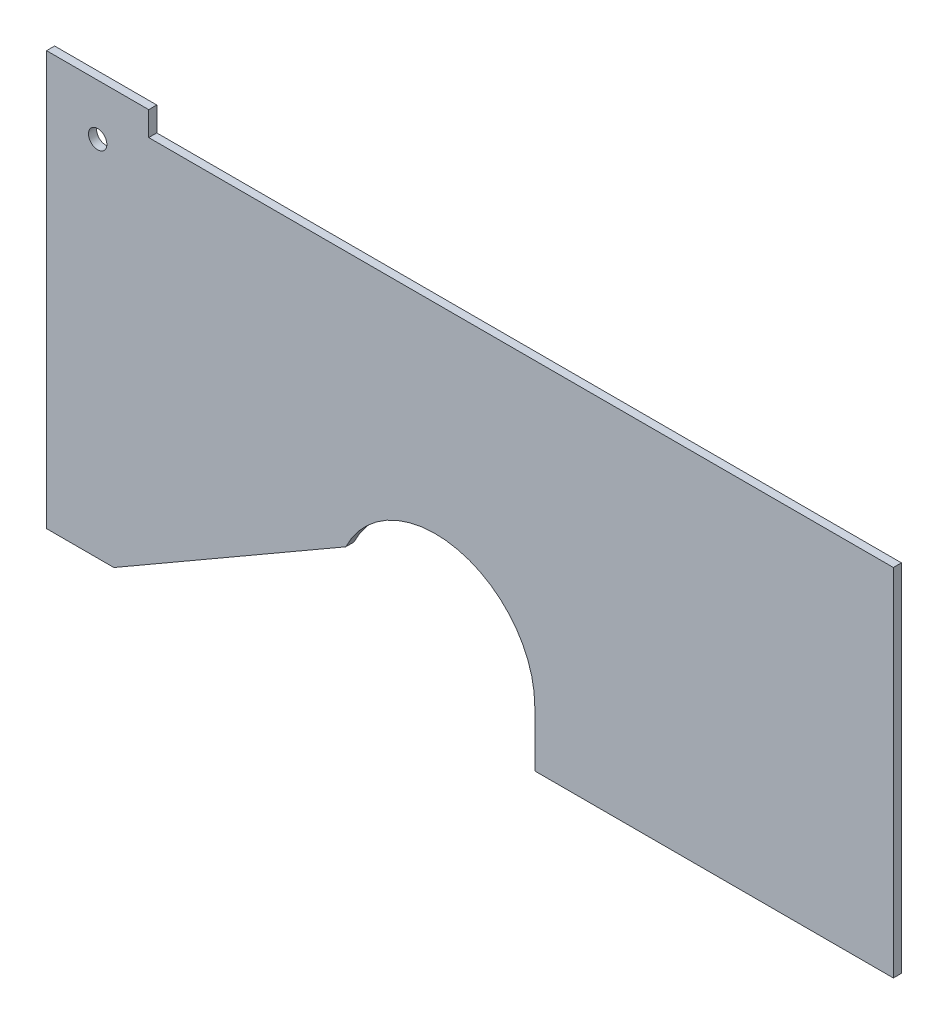
SolidWorks part; units mm, degrees
ref_plane "Front Plane" through (0, 0, 0) normal (0, 0, 1) x (1, 0, 0)
ref_plane "Top Plane" through (0, 0, 0) normal (0, 1, 0) x (1, 0, 0)
ref_plane "Right Plane" through (0, 0, 0) normal (1, 0, 0) x (0, 0, -1)
sketch "Sketch2" plane through (0, 0, 0) normal (0, 0, 1) x (1, 0, 0)
  line L0 (25.0304, 0) -> (111.2865, 49.8)
  line L1 (0, 0) -> (25.0304, 0)
  line L2 (0, 0) -> (0, 154)
  line L4 (315, 0) -> (315, 145)
  line L5 (181.6, 33.7) -> (181.6, 0)
  line L6 (181.6, 0) -> (315, 0)
  line L7 (19, 135) -> (19, 164.3674) construction
  line L11 (38, 145) -> (315, 145)
  line L12 (0, 154) -> (19, 154)
  line L13 (19, 154) -> (38, 154)
  line L14 (38, 154) -> (38, 145)
  line L15 (19, 135) -> (50019, 135) construction
  line L20 (19, 135) -> (19, -49865) construction
  circle A0 centre (19, 135) radius 3.425
  arc A1 (181.6, 33.7) -> (111.2865, 49.8) centre (144.6, 33.7) ccw
  point P19 (19, 154)
  dimension "D3" = 135
  dimension "D4" = 19
  dimension "D5" = 6.85
  dimension "D6" = 74
  dimension "D7" = 170.4
  dimension "D8" = 33.7
  dimension "D1" = 315
  dimension "D2" = 154
  dimension "D9" = 30
  dimension "D10" = 99.6
  dimension "D11" = 19
extrude "Boss-Extrude2" add sketch "Sketch2" along normal blind 3
sketch "Sketch3" plane through (0, 0, 3) normal (0, 0, 1) x (1, 0, 0)
  line L0 (315, 0) -> (315, 145) construction
  line L1 (181.6, 0) -> (315, 0)
  line L2 (181.6, 0) -> (181.6, 12.75)
  line L3 (181.6, 12.75) -> (315, 12.75)
  line L4 (315, 0) -> (315, 12.75)
  dimension "D1" = 12.75
extrude "Cut-Extrude1" cut sketch "Sketch3" against normal through all
sketch "Sketch4" plane through (0, 0, 3) normal (0, 0, 1) x (1, 0, 0)
  line L0 (19, 135) -> (19, -49865) construction
  line L1 (19, 135) -> (-49981, 135) construction
